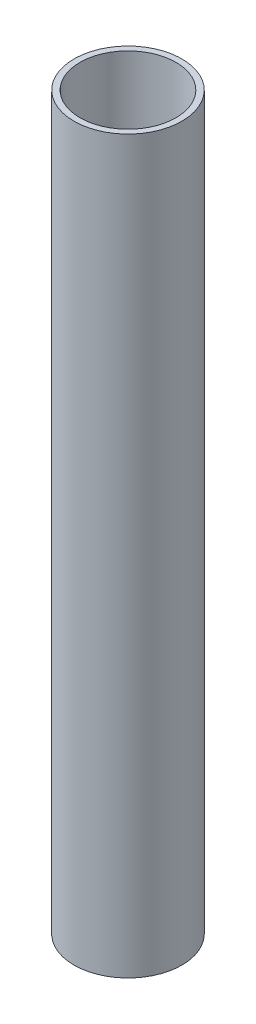
SolidWorks part; units mm, degrees
ref_plane "Front Plane" through (0, 0, 0) normal (0, 0, 1) x (1, 0, 0)
ref_plane "Top Plane" through (0, 0, 0) normal (0, 1, 0) x (1, 0, 0)
ref_plane "Right Plane" through (0, 0, 0) normal (1, 0, 0) x (0, 0, -1)
sketch "Sketch1" plane through (0, 0, 0) normal (0, 1, 0) x (1, 0, 0)
  circle A0 centre (0, 0) radius 15
  circle A1 centre (0, 0) radius 13.349
  dimension "D1" = 30
  dimension "D2" = 1.651
extrude "Boss-Extrude1" add sketch "Sketch1" along normal blind 203.2
